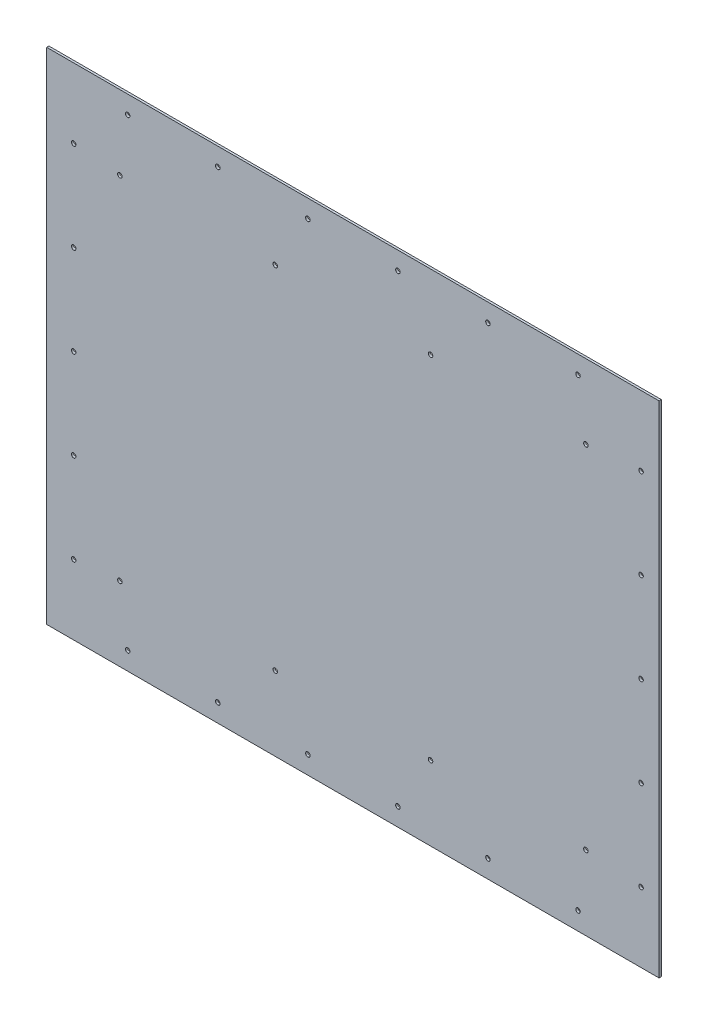
SolidWorks part; units mm, degrees
material "6061-T6 (SS)"
ref_plane "Front" through (0, 0, 0) normal (0, 0, 1) x (1, 0, 0)
ref_plane "Top" through (0, 0, 0) normal (0, 1, 0) x (1, 0, 0)
ref_plane "Right" through (0, 0, 0) normal (1, 0, 0) x (0, 0, -1)
sketch "Sketch1" plane through (0, 0, 0) normal (0, 0, 1) x (1, 0, 0)
  line L1 (0, 0) -> (863.6, 0)
  line L2 (0, 0) -> (0, 704.85)
  line L3 (0, 704.85) -> (863.6, 704.85)
  line L4 (863.6, 0) -> (863.6, 704.85)
  dimension "D1" = 704.85
  dimension "D2" = 863.6
extrude "Boss-Extrude1" add sketch "Sketch1" along normal blind 3.175
hole_wizard "1/4 (0.25) Diameter Hole4" positions "Sketch2" profile "Sketch3" hole size "1/4" standard "ANSI Inch" end condition through all
sketch "Sketch2" plane through (0, 0, 3.175) normal (0, 0, 1) x (1, 0, 0)
  line L0 (0, 704.85) -> (0, 0) construction
  line L1 (0, 0) -> (863.6, 0) construction
  point P0 (38.1, 98.425)
  dimension "D1" = 38.1
  dimension "D2" = 98.425
sketch "Sketch3" plane through (38.1, 98.425, 3.175) normal (1, 0, 0) x (0, -1, 0)
  line L0 (0, 0) -> (0, 3.175)
  line L1 (0, 3.175) -> (3.175, 3.175)
  line L2 (3.175, 3.175) -> (3.175, 0)
  line L5 (3.175, 0) -> (0, 0)
  line L11 (0, -6.35) -> (0, 107.95) construction
  dimension "Thru Hole Dia." = 6.35
  dimension "Thru Hole Depth" = 3.175
pattern_linear "LPattern1" count 5 spacing 127 along (0, 1, 0) of "1/4 (0.25) Diameter Hole4"
hole_wizard "1/4 (0.25) Diameter Hole2" positions "Sketch6" profile "Sketch7" hole size "1/4" standard "ANSI Inch" end condition through all
sketch "Sketch6" plane through (0, 0, 3.175) normal (0, 0, 1) x (1, 0, 0)
  line L0 (0, 0) -> (863.6, 0) construction
  line L1 (863.6, 0) -> (863.6, 704.85) construction
  point P0 (749.3, 25.4)
  dimension "D1" = 25.4
  dimension "D2" = 114.3
sketch "Sketch7" plane through (749.3, 25.4, 3.175) normal (1, 0, 0) x (0, -1, 0)
  line L0 (0, 0) -> (0, 3.175)
  line L1 (0, 3.175) -> (3.175, 3.175)
  line L2 (3.175, 3.175) -> (3.175, 0)
  line L5 (3.175, 0) -> (0, 0)
  line L11 (0, -6.35) -> (0, 107.95) construction
  dimension "Thru Hole Dia." = 6.35
  dimension "Thru Hole Depth" = 3.175
pattern_linear "LPattern2" count 6 spacing 127 along (-1, 0, 0) count 2 spacing 654.05 along (0, 1, 0) of "1/4 (0.25) Diameter Hole2"
hole_wizard "1/4 (0.25) Diameter Hole3" positions "Sketch8" profile "Sketch9" hole size "1/4" standard "ANSI Inch" end condition up to next
sketch "Sketch8" plane through (0, 0, 3.175) normal (0, 0, 1) x (1, 0, 0)
  line L0 (863.6, 0) -> (863.6, 704.85) construction
  line L1 (0, 0) -> (863.6, 0) construction
  point P0 (838.2, 98.425)
  dimension "D1" = 25.4
  dimension "D2" = 98.425
sketch "Sketch9" plane through (838.2, 98.425, 3.175) normal (1, 0, 0) x (0, -1, 0)
  line L0 (0, 0) -> (0, 3.175)
  line L1 (0, 3.175) -> (3.175, 3.175)
  line L2 (3.175, 3.175) -> (3.175, 0)
  line L5 (3.175, 0) -> (0, 0)
  line L11 (0, -6.35) -> (0, 107.95) construction
  dimension "Thru Hole Dia." = 6.35
  dimension "Thru Hole Depth" = 3.175
pattern_linear "LPattern3" count 5 spacing 127 along (0, 1, 0) of "1/4 (0.25) Diameter Hole3"
hole_wizard "1/4 (0.25) Diameter Hole5" positions "Sketch10" profile "Sketch11" hole size "1/4" standard "ANSI Inch" end condition through all
sketch "Sketch10" plane through (0, 0, 3.175) normal (0, 0, 1) x (1, 0, 0)
  line L0 (0, 704.85) -> (0, 0) construction
  line L1 (0, 0) -> (863.6, 0) construction
  point P0 (103.1875, 104.775)
  dimension "D1" = 103.1875
  dimension "D2" = 104.775
sketch "Sketch11" plane through (103.1875, 104.775, 3.175) normal (1, 0, 0) x (0, -1, 0)
  line L0 (0, 0) -> (0, 3.175)
  line L1 (0, 3.175) -> (3.175, 3.175)
  line L2 (3.175, 3.175) -> (3.175, 0)
  line L5 (3.175, 0) -> (0, 0)
  line L11 (0, -6.35) -> (0, 107.95) construction
  dimension "Thru Hole Dia." = 6.35
  dimension "Thru Hole Depth" = 3.175
pattern_linear "LPattern4" count 4 spacing 219.075 along (1, 0, 0) count 2 spacing 495.3 along (0, 1, 0) of "1/4 (0.25) Diameter Hole5"
